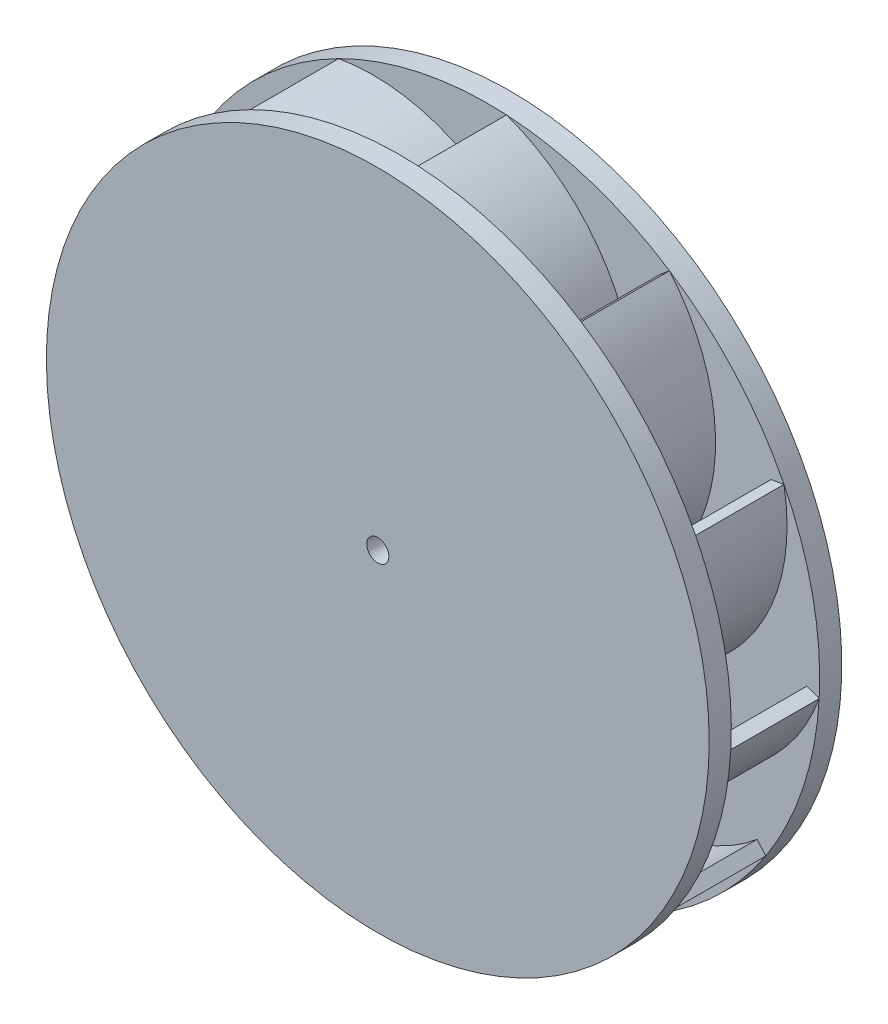
SolidWorks part; units mm, degrees
ref_plane "前视基准面" through (0, 0, 0) normal (0, 0, 1) x (1, 0, 0)
ref_plane "上视基准面" through (0, 0, 0) normal (0, 1, 0) x (1, 0, 0)
ref_plane "右视基准面" through (0, 0, 0) normal (1, 0, 0) x (0, 0, -1)
other "Configuration Table"
sketch "草图1" plane through (0, 0, 0) normal (0, 0, 1) x (1, 0, 0)
  circle A0 centre (0, 0) radius 15
extrude "凸台-拉伸1" add sketch "草图1" along normal blind 1
sketch "草图2" plane through (0, 0, 0) normal (0, 0, -1) x (-1, 0, 0)
  line L0 (0, 0) -> (0, 15) construction
  circle A0 centre (0, 0) radius 15 construction
  circle A1 centre (0, 0) radius 7 construction
  arc A2 (0, 7) -> (12.5578, 8.2037) centre (6.8668, 1.4691) cw
  arc A3 (3.5, 6.0622) -> (14.9773, 0.8257) centre (6.6813, -2.1611) cw
  arc A4 (6.0622, 3.5) -> (13.3835, -6.7735) centre (4.7056, -5.2123) cw
  arc A5 (7, 0) -> (8.2037, -12.5578) centre (1.4691, -6.8668) cw
  arc A6 (6.0622, -3.5) -> (0.8257, -14.9773) centre (-2.1611, -6.6813) cw
  arc A7 (3.5, -6.0622) -> (-6.7735, -13.3835) centre (-5.2123, -4.7056) cw
  arc A8 (0, -7) -> (-12.5578, -8.2037) centre (-6.8668, -1.4691) cw
  arc A9 (-3.5, -6.0622) -> (-14.9773, -0.8257) centre (-6.6813, 2.1611) cw
  arc A10 (-6.0622, -3.5) -> (-13.3835, 6.7735) centre (-4.7056, 5.2123) cw
  arc A11 (-7, 0) -> (-8.2037, 12.5578) centre (-1.4691, 6.8668) cw
  arc A12 (-6.0622, 3.5) -> (-0.8257, 14.9773) centre (2.1611, 6.6813) cw
  arc A13 (-3.5, 6.0622) -> (6.7735, 13.3835) centre (5.2123, 4.7056) cw
  point P45 (0, 0)
  dimension "D1" = 12
extrude "拉伸-薄壁4" add sketch "草图2" along normal blind 5 thin
sketch "草图3" plane through (0, 0, 0) normal (0, 0, -1) x (-1, 0, 0)
  circle A0 centre (0, 0) radius 2
extrude "凸台-拉伸2" add sketch "草图3" along normal blind 4
fillet "圆角1" radius 2 1 edges at (2, 0, 0)
fillet "圆角2" radius 1 1 edges at (-2, 0, -4)
sketch "草图4" plane through (0, 0, 1) normal (0, 0, 1) x (1, 0, 0)
  circle A0 centre (0, 0) radius 0.5
extrude "切除-拉伸1" cut sketch "草图4" against normal blind 5
sketch "草图5" plane through (0, 0, -5) normal (0, 0, -1) x (-1, 0, 0)
  circle A0 centre (0, 0) radius 15
extrude "凸台-拉伸3" add sketch "草图5" against normal blind 1
sketch "草图6" plane through (0, 0, -5) normal (0, 0, -1) x (-1, 0, 0)
  circle A0 centre (0, 0) radius 8
  circle A1 centre (0, 0) radius 7.2
extrude "凸台-拉伸4" add sketch "草图6" along normal blind 1
sketch "草图7" plane through (0, 0, -5) normal (0, 0, -1) x (-1, 0, 0)
  circle A0 centre (0, 0) radius 7.6
extrude "切除-拉伸2" cut sketch "草图7" against normal blind 1
